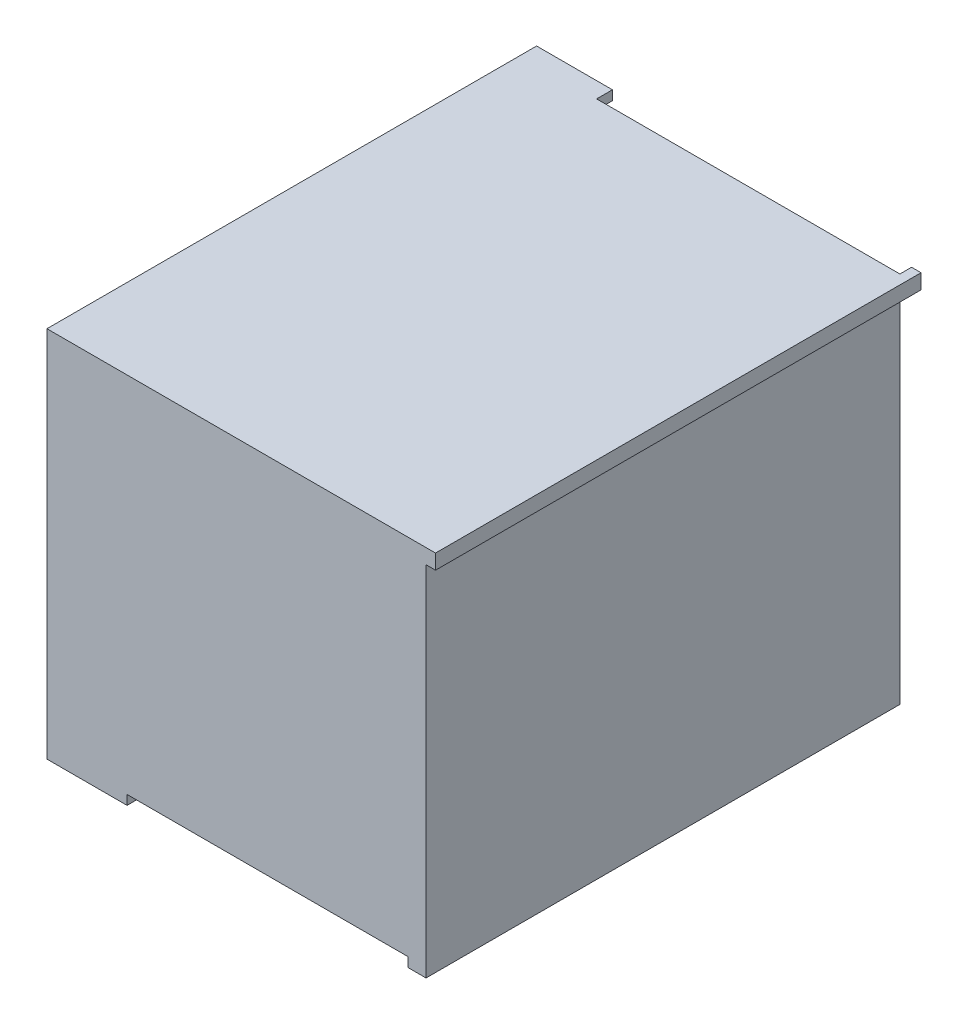
SolidWorks part; units mm, degrees
ref_plane "Front Plane" through (0, 0, 0) normal (0, 0, 1) x (1, 0, 0)
ref_plane "Top Plane" through (0, 0, 0) normal (0, 1, 0) x (1, 0, 0)
ref_plane "Right Plane" through (0, 0, 0) normal (1, 0, 0) x (0, 0, -1)
sketch "Sketch1" plane through (0, 0, 0) normal (0, 0, 1) x (1, 0, 0)
  line L1 (-1142.1965, 419.0751) -> (57.8035, 419.0751)
  line L2 (-1142.1965, 419.0751) -> (-1142.1965, -730.9249)
  line L3 (-1142.1965, -730.9249) -> (57.8035, -730.9249)
  line L4 (57.8035, 419.0751) -> (57.8035, -730.9249)
  dimension "D1" = 1200
  dimension "D2" = 1150
extrude "Boss-Extrude1" add sketch "Sketch1" along normal blind 1500
sketch "Sketch2" plane through (0, -730.9249, 0) normal (0, -1, 0) x (1, 0, 0)
  line L0 (-1142.1965, 1500) -> (57.8035, 1500) construction
  line L1 (57.8035, 0) -> (0, 0)
  line L2 (57.8035, 0) -> (57.8035, 1500)
  line L3 (57.8035, 1500) -> (0, 1500)
  line L4 (0, 0) -> (0, 1500)
  line L5 (-1142.1965, 0) -> (57.8035, 0) construction
  line L6 (-1142.1965, 1500) -> (-888.6109, 1500)
  line L7 (-1142.1965, 1500) -> (-1142.1965, 0)
  line L8 (-1142.1965, 0) -> (-888.6109, 0)
  line L9 (-888.6109, 1500) -> (-888.6109, 0)
extrude "Boss-Extrude2" add sketch "Sketch2" along normal blind 30
sketch "Sketch3" plane through (57.8035, 0, 0) normal (1, 0, 0) x (0, 0, -1)
  line L1 (-1500, 419.0751) -> (36.9465, 419.0751)
  line L2 (-1500, 419.0751) -> (-1500, 371.9933)
  line L3 (-1500, 371.9933) -> (36.9465, 371.9933)
  line L4 (36.9465, 419.0751) -> (36.9465, 371.9933)
extrude "Boss-Extrude3" add sketch "Sketch3" along normal blind 30
sketch "Sketch4" plane through (0, 419.0751, 0) normal (0, 1, 0) x (1, 0, 0)
  line L1 (-1142.1965, -1500) -> (-902.2032, -1500)
  line L2 (-1142.1965, -1500) -> (-1142.1965, 50)
  line L3 (-1142.1965, 50) -> (-902.2032, 50)
  line L4 (-902.2032, -1500) -> (-902.2032, 50)
  dimension "D1" = 1550
extrude "Boss-Extrude5" add sketch "Sketch4" against normal blind 30
